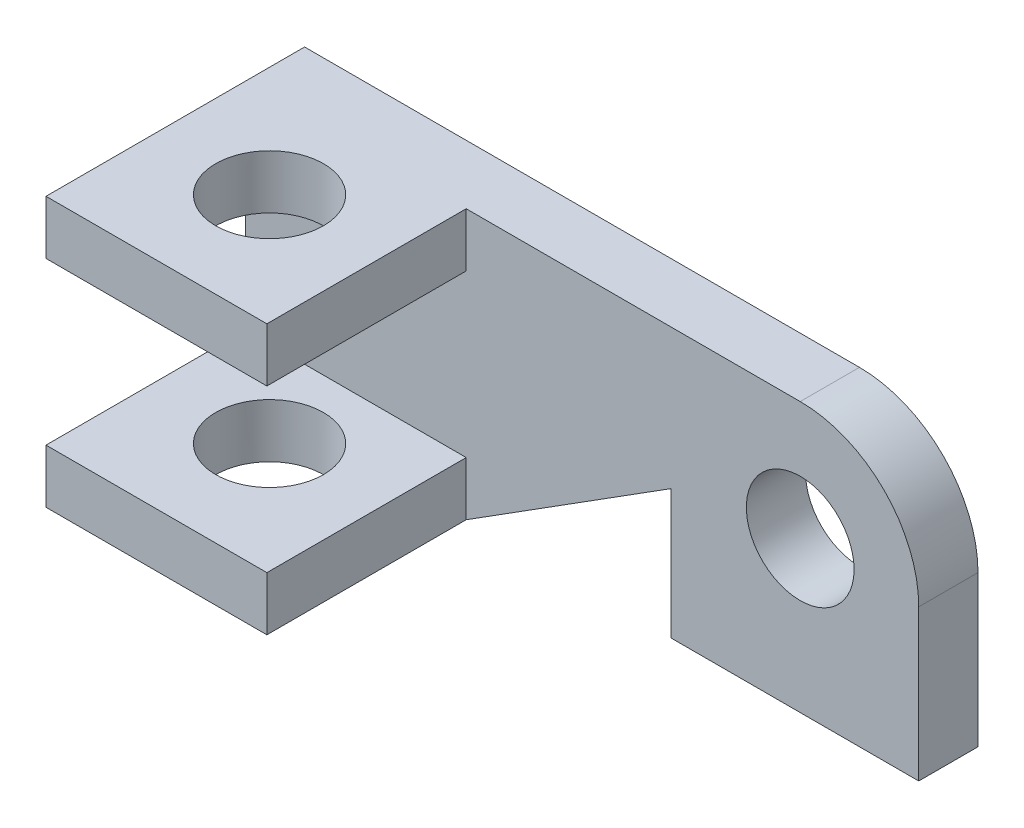
SolidWorks part; units mm, degrees
ref_plane "Front Plane" through (0, 0, 0) normal (0, 0, 1) x (1, 0, 0)
ref_plane "Top Plane" through (0, 0, 0) normal (0, 1, 0) x (1, 0, 0)
ref_plane "Right Plane" through (0, 0, 0) normal (1, 0, 0) x (0, 0, -1)
sketch "Sketch1" plane through (0, 0, 0) normal (0, 0, 1) x (1, 0, 0)
  line L0 (-24, -28) -> (22, -28)
  line L1 (22, -28) -> (22, 0)
  line L2 (0, 22) -> (-103, 22)
  line L5 (-62, -28) -> (-24, -4)
  line L6 (-24, -4) -> (-24, -28)
  line L7 (-62, -28) -> (-103, -28)
  line L9 (-103, 22) -> (-103, -28)
  circle A0 centre (0, 0) radius 10
  arc A1 (0, 22) -> (22, 0) centre (0, 0) cw
  point P12 (22, 22)
  dimension "D1" = 20
  dimension "D9" = 22
  dimension "D2" = 46
  dimension "D3" = 38
  dimension "D4" = 50
  dimension "D5" = 125
  dimension "D6" = 28
  dimension "D7" = 24
  dimension "D8" = 22
extrude "Boss-Extrude1" add sketch "Sketch1" along normal blind 11
sketch "Sketch2" plane through (0, 0, 11) normal (0, 0, 1) x (1, 0, 0)
  line L0 (-117.2922, -3) -> (40.4235, -3) construction
  line L1 (-103, 22) -> (-62, 22)
  line L2 (-103, 22) -> (-103, 12)
  line L3 (-103, 12) -> (-62, 12)
  line L4 (-62, 22) -> (-62, 12)
  line L5 (-103, -18) -> (-62, -18)
  line L6 (-62, -28) -> (-62, -18)
  line L7 (-103, -28) -> (-62, -28)
  line L8 (-103, -28) -> (-103, -18)
  line L10 (-103, 22) -> (-103, -28) construction
  point P14 (-103, -3)
  dimension "D1" = 41
  dimension "D2" = 10
extrude "Boss-Extrude2" add sketch "Sketch2" along normal blind 37
sketch "Sketch3" plane through (0, -28, 0) normal (0, -1, 0) x (1, 0, 0)
  line L0 (-103, 48) -> (-103, 0) construction
  line L1 (-103, 48) -> (-62, 48) construction
  circle A0 centre (-82.5, 27) radius 10
  dimension "D3" = 20
  dimension "D1" = 20.5
  dimension "D2" = 21
extrude "Cut-Extrude1" cut sketch "Sketch3" against normal through all
